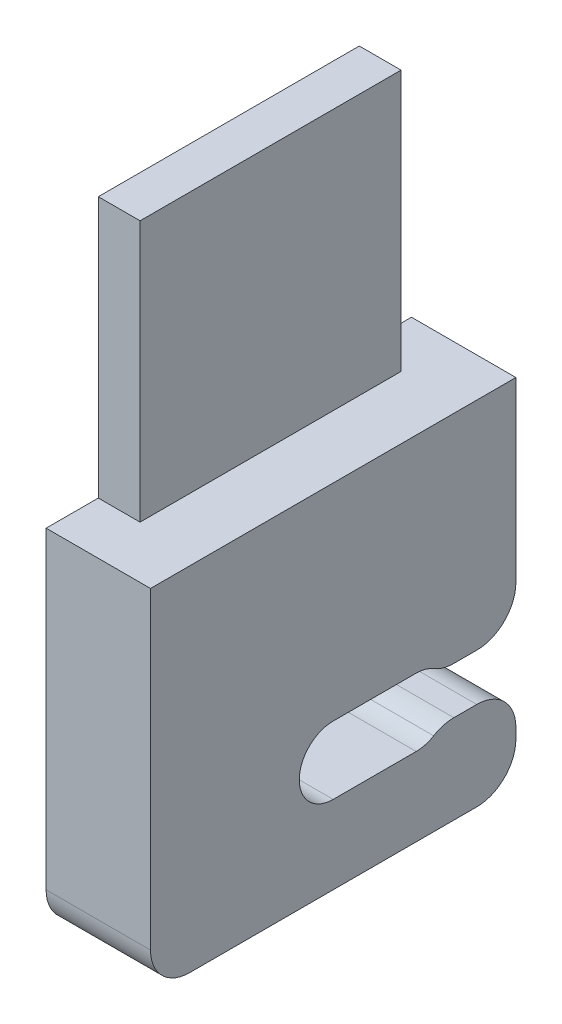
SolidWorks part; units mm, degrees
ref_plane "Front Plane" through (0, 0, 0) normal (0, 0, 1) x (1, 0, 0)
ref_plane "Top Plane" through (0, 0, 0) normal (0, 1, 0) x (1, 0, 0)
ref_plane "Right Plane" through (0, 0, 0) normal (1, 0, 0) x (0, 0, -1)
sketch "Sketch1" plane through (0, 0, 0) normal (1, 0, 0) x (0, 0, -1)
  line L1 (0, 0) -> (10, 0)
  line L2 (0, 0) -> (0, -10)
  line L3 (0, -10) -> (10, -10)
  line L4 (10, 0) -> (10, -10)
  dimension "D1" = 10
  dimension "D2" = 10
extrude "Boss-Extrude1" add sketch "Sketch1" along normal blind 1.6
sketch "Sketch2" plane through (0, 0, 0) normal (0, 0, 1) x (1, 0, 0)
  line L3 (1.2, -12) -> (0, -12)
  line L4 (0, -10) -> (0, -12)
  line L5 (1.6, -10) -> (4, -10)
  line L7 (2.8, -12) -> (4, -12)
  line L8 (4, -10) -> (4, -12)
  line L9 (1.2, -12) -> (2.8, -12)
  line L11 (0, -10) -> (1.6, -10)
  point P10 (0, 0)
  line M8 (0, -10) -> (1.6, -10)
  dimension "D1" = 4
  dimension "D2" = 2
  dimension "D3" = 0
extrude "Boss-Extrude2" add sketch "Sketch2" against normal up to surface (10 mm away) contours L3 L9 L7 L8 L5 L4 M8 up to face at (0.8, -5, -10)
sketch "Sketch3" plane through (0, 0, 0) normal (0, 0, 1) x (1, 0, 0)
  line L9 (4, -10) -> (0, -10)
  line L10 (4, -10) -> (4, -12)
  line L11 (4, -12) -> (0, -12)
  line L12 (0, -10) -> (0, -12)
extrude "Boss-Extrude3" add sketch "Sketch3" along normal blind 2
sketch "Sketch4" plane through (0, 0, -10) normal (0, 0, -1) x (-1, 0, 0)
  line L0 (-4, -10) -> (-1.6, -10) construction
  line L5 (-4, -10) -> (0, -10)
  line L6 (-4, -10) -> (-4, -12)
  line L7 (-4, -12) -> (0, -12)
  line L8 (0, -10) -> (0, -12)
  line L9 (-4, -12) -> (-4, -10) construction
  line L10 (0, -12) -> (-4, -12) construction
  line L11 (0, -12) -> (0, 0) construction
extrude "Boss-Extrude4" add sketch "Sketch4" along normal blind 2
sketch "Sketch5" plane through (4, 0, 0) normal (1, 0, 0) x (0, 0, -1)
  line L0 (12, -10) -> (12, -12) construction
  line L1 (-2, -12) -> (12, -12)
  line L2 (-2, -12) -> (-2, -22)
  line L3 (-0.5, -23.5) -> (10.5, -23.5)
  line L4 (12, -12) -> (12, -22)
  line L12 (-2, -16.6655) -> (-2, -18.3)
  line L16 (-2, -16.6655) -> (-2, -20.1)
  line L17 (8.18, -18.3) -> (12, -18.3)
  line L19 (8.18, -20.1) -> (12, -20.1)
  line L20 (12, -18.3) -> (12, -20.1)
  line L21 (5, -17.9) -> (8.18, -17.9)
  line L23 (5, -20.5) -> (8.18, -20.5)
  circle A0 centre (5, -19.2) radius 1.3
  circle A1 centre (8.18, -19.2) radius 1.3
  arc A2 (10.5, -23.5) -> (12, -22) centre (10.5, -22) ccw
  arc A3 (-2, -22) -> (-0.5, -23.5) centre (-0.5, -22) ccw
  point P22 (12, -23.5)
  dimension "D2" = 2.6
  dimension "D3" = 2.6
  dimension "D7" = 1.5
  dimension "D1" = 11.5
  dimension "D4" = 0.9
  dimension "D5" = 0.9
  dimension "D6" = 4.3
  dimension "D8" = 3.82
  dimension "D9" = 7
extrude "Boss-Extrude5" add sketch "Sketch5" against normal up to surface (4 mm away)
fillet "Fillet2" radius 1.5 4 edges at (2, -18.3, -12) (2, -18.3, -9.1181) (2, -20.1, -9.1181) (2, -20.1, -12)
